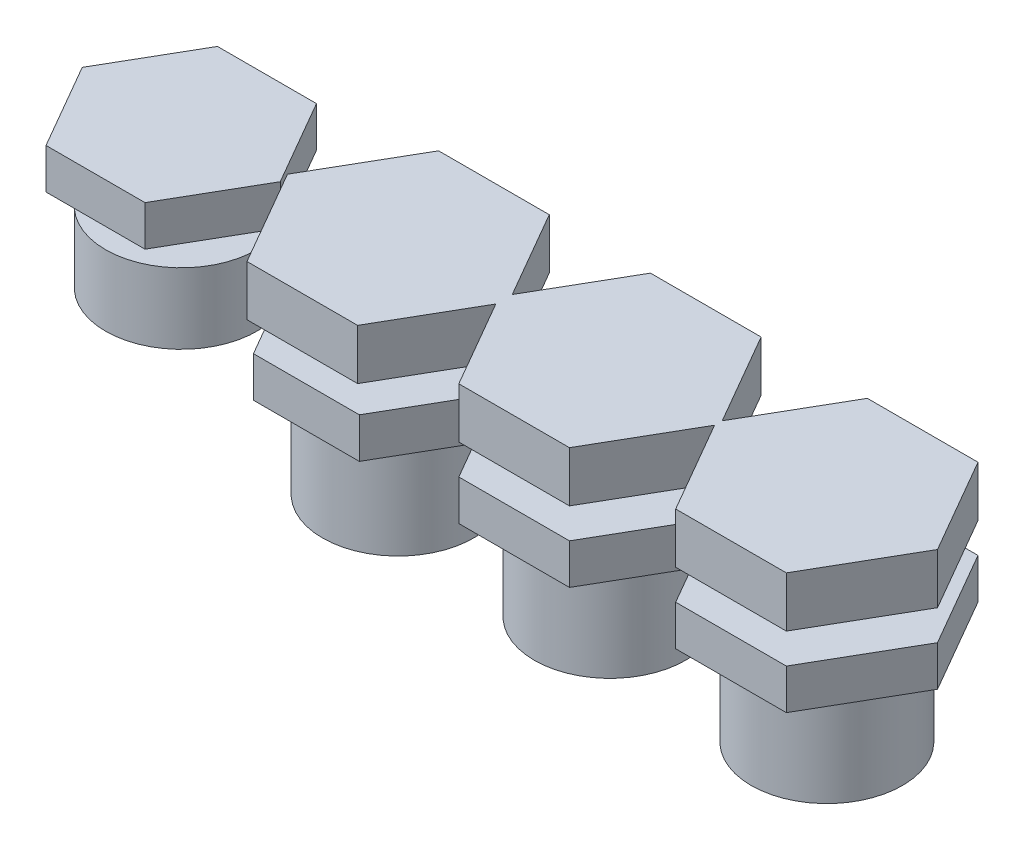
SolidWorks part; units mm, degrees
ref_plane "Front Plane" through (0, 0, 0) normal (0, 0, 1) x (1, 0, 0)
ref_plane "Top Plane" through (0, 0, 0) normal (0, 1, 0) x (1, 0, 0)
ref_plane "Right Plane" through (0, 0, 0) normal (1, 0, 0) x (0, 0, -1)
ref_plane "Plane1" through (0, -86.5, 0) normal (0, 1, 0) x (1, 0, 0)
sketch "Sketch1" plane through (0, -86.5, 0) normal (0, 1, 0) x (1, 0, 0)
  line L1 (0, -26) -> (-5.25, -16.9067)
  line L2 (-5.25, -16.9067) -> (-15.75, -16.9067)
  line L3 (-15.75, -16.9067) -> (-21, -26)
  line L4 (-21, -26) -> (-15.75, -35.0933)
  line L5 (-15.75, -35.0933) -> (-5.25, -35.0933)
  line L6 (-5.25, -35.0933) -> (0, -26)
  circle A0 centre (-10.5, -26) radius 9.0933 construction
extrude "Boss-Extrude1" add sketch "Sketch1" along normal blind 4
ref_plane "Plane2" through (0, -96.5, 0) normal (0, 1, 0) x (1, 0, 0)
sketch "Sketch2" plane through (0, -96.5, 0) normal (0, 1, 0) x (1, 0, 0)
  circle A0 centre (-10.5, -26) radius 7.5
extrude "Boss-Extrude2" add sketch "Sketch2" along normal blind 10
ref_plane "Plane3" through (0, -79.5, 0) normal (0, 1, 0) x (1, 0, 0)
sketch "Sketch3" plane through (0, -79.5, 0) normal (0, 1, 0) x (1, 0, 0)
  line L1 (0.4697, -26) -> (-5.0152, -16.5)
  line L2 (-5.0152, -16.5) -> (-15.9848, -16.5)
  line L3 (-15.9848, -16.5) -> (-21.4697, -26)
  line L4 (-21.4697, -26) -> (-15.9848, -35.5)
  line L5 (-15.9848, -35.5) -> (-5.0152, -35.5)
  line L6 (-5.0152, -35.5) -> (0.4697, -26)
  circle A0 centre (-10.5, -26) radius 9.5 construction
extrude "Boss-Extrude3" add sketch "Sketch3" along normal blind 5
sketch "Sketch4" plane through (0, -86.5, 0) normal (0, 1, 0) x (1, 0, 0)
  line L1 (21.4697, -26) -> (15.9848, -16.5)
  line L2 (15.9848, -16.5) -> (5.0152, -16.5)
  line L3 (5.0152, -16.5) -> (-0.4697, -26)
  line L4 (-0.4697, -26) -> (5.0152, -35.5)
  line L5 (5.0152, -35.5) -> (15.9848, -35.5)
  line L6 (15.9848, -35.5) -> (21.4697, -26)
  circle A0 centre (10.5, -26) radius 9.5 construction
extrude "Boss-Extrude4" add sketch "Sketch4" along normal blind 4
sketch "Sketch5" plane through (0, -96.5, 0) normal (0, 1, 0) x (1, 0, 0)
  circle A0 centre (10.5, -26) radius 7.5
extrude "Boss-Extrude5" add sketch "Sketch5" along normal blind 10
sketch "Sketch6" plane through (0, -79.5, 0) normal (0, 1, 0) x (1, 0, 0)
  line L1 (21.4697, -26) -> (15.9848, -16.5)
  line L2 (15.9848, -16.5) -> (5.0152, -16.5)
  line L3 (5.0152, -16.5) -> (-0.4697, -26)
  line L4 (-0.4697, -26) -> (5.0152, -35.5)
  line L5 (5.0152, -35.5) -> (15.9848, -35.5)
  line L6 (15.9848, -35.5) -> (21.4697, -26)
  circle A0 centre (10.5, -26) radius 9.5 construction
extrude "Boss-Extrude6" add sketch "Sketch6" along normal blind 5
sketch "Sketch7" plane through (0, -86.5, 0) normal (0, 1, 0) x (1, 0, 0)
  line L1 (42.9697, -26) -> (37.4848, -16.5)
  line L2 (37.4848, -16.5) -> (26.5152, -16.5)
  line L3 (26.5152, -16.5) -> (21.0303, -26)
  line L4 (21.0303, -26) -> (26.5152, -35.5)
  line L5 (26.5152, -35.5) -> (37.4848, -35.5)
  line L6 (37.4848, -35.5) -> (42.9697, -26)
  circle A0 centre (32, -26) radius 9.5 construction
extrude "Boss-Extrude7" add sketch "Sketch7" along normal blind 4
sketch "Sketch8" plane through (0, -96.5, 0) normal (0, 1, 0) x (1, 0, 0)
  circle A0 centre (32, -26) radius 7.5
extrude "Boss-Extrude8" add sketch "Sketch8" along normal blind 10
sketch "Sketch9" plane through (0, -79.5, 0) normal (0, 1, 0) x (1, 0, 0)
  line L1 (42.9697, -26) -> (37.4848, -16.5)
  line L2 (37.4848, -16.5) -> (26.5152, -16.5)
  line L3 (26.5152, -16.5) -> (21.0303, -26)
  line L4 (21.0303, -26) -> (26.5152, -35.5)
  line L5 (26.5152, -35.5) -> (37.4848, -35.5)
  line L6 (37.4848, -35.5) -> (42.9697, -26)
  circle A0 centre (32, -26) radius 9.5 construction
extrude "Boss-Extrude9" add sketch "Sketch9" along normal blind 5
ref_plane "Plane4" through (0, -89.5, 0) normal (0, 1, 0) x (1, 0, 0)
sketch "Sketch10" plane through (0, -89.5, 0) normal (0, 1, 0) x (1, 0, 0)
  circle A0 centre (-32, -26) radius 7.5
extrude "Boss-Extrude10" add sketch "Sketch10" along normal blind 7
sketch "Sketch11" plane through (0, -79.5, 0) normal (0, 1, 0) x (1, 0, 0)
  line L1 (-22.185, -26) -> (-27.0925, -17.5)
  line L2 (-27.0925, -17.5) -> (-36.9075, -17.5)
  line L3 (-36.9075, -17.5) -> (-41.815, -26)
  line L4 (-41.815, -26) -> (-36.9075, -34.5)
  line L5 (-36.9075, -34.5) -> (-27.0925, -34.5)
  line L6 (-27.0925, -34.5) -> (-22.185, -26)
  circle A0 centre (-32, -26) radius 8.5 construction
extrude "Boss-Extrude11" add sketch "Sketch11" along normal blind 4
